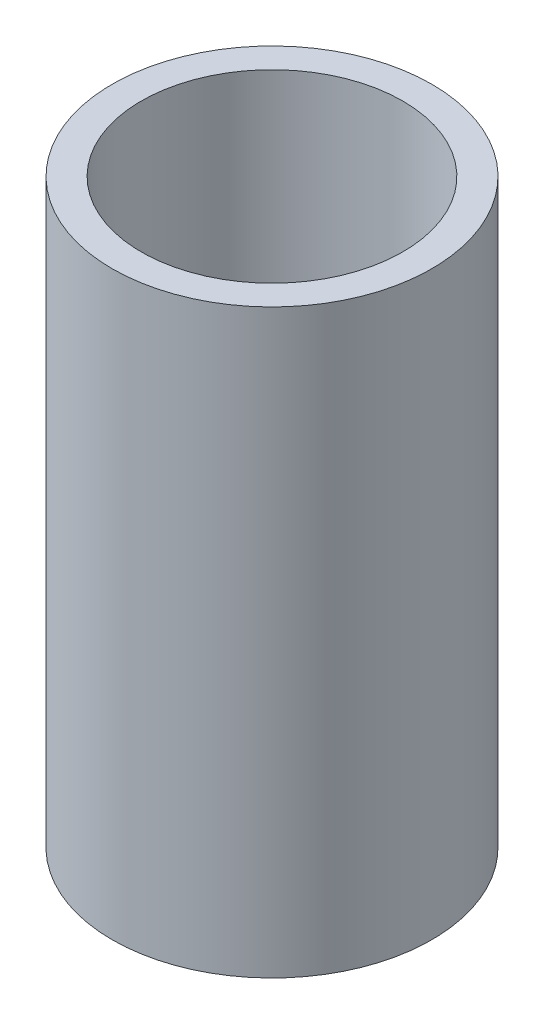
SolidWorks part; units mm, degrees
ref_plane "Спереди" through (0, 0, 0) normal (0, 0, 1) x (1, 0, 0)
ref_plane "Сверху" through (0, 0, 0) normal (0, 1, 0) x (1, 0, 0)
ref_plane "Справа" through (0, 0, 0) normal (1, 0, 0) x (0, 0, -1)
sketch "Эскиз1" plane through (0, 0, 0) normal (0, 0, 1) x (1, 0, 0)
  line L0 (0, -110.6031) -> (0, 130.0787) construction
  line L1 (45, 100) -> (55, 100)
  line L2 (45, 100) -> (45, -100)
  line L3 (45, -100) -> (55, -100)
  line L4 (55, 100) -> (55, -100)
  point P4 (45, 0)
  dimension "D1" = 10
  dimension "D2" = 200
  dimension "D3" = 45
revolve "Повернуть1" add sketch "Эскиз1" angle 360 about L0
surface "Поверхность-Промежуточная поверхность1" parameters "D0"=10000
surface "Поверхность-Промежуточная поверхность2" [suppressed] parameters "D0"=50000
